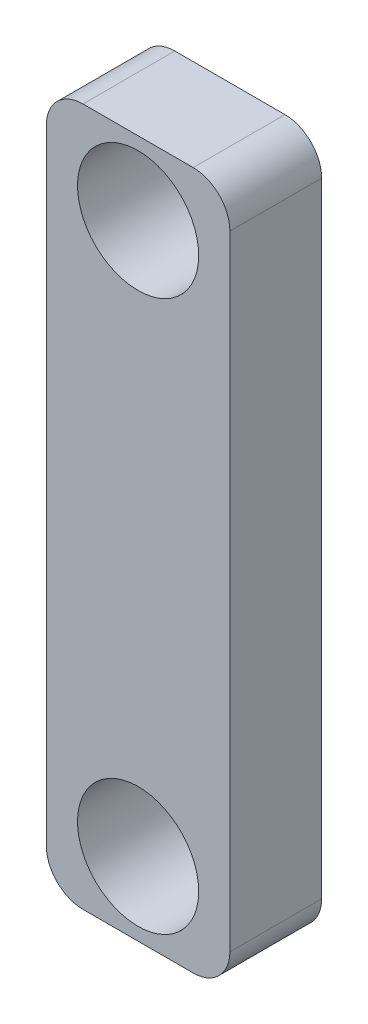
SolidWorks part; units mm, degrees
ref_plane "前视基准面" through (0, 0, 0) normal (0, 0, 1) x (1, 0, 0)
ref_plane "上视基准面" through (0, 0, 0) normal (0, 1, 0) x (1, 0, 0)
ref_plane "右视基准面" through (0, 0, 0) normal (1, 0, 0) x (0, 0, -1)
sketch "草图1" plane through (0, 0, 0) normal (0, 0, 1) x (1, 0, 0)
  line L1 (0, 0) -> (50, 0)
  line L2 (0, 0) -> (0, 190)
  line L3 (0, 190) -> (50, 190)
  line L4 (50, 0) -> (50, 190)
  circle A0 centre (25, 170) radius 16.5
  circle A1 centre (25, 20) radius 16.5
  dimension "D5" = 33
  dimension "D6" = 33
  dimension "D1" = 190
  dimension "D2" = 50
  dimension "D3" = 20
  dimension "D4" = 20
  dimension "D7" = 25
  dimension "D8" = 25
extrude "凸台-拉伸1" add sketch "草图1" along normal blind 25
fillet "圆角1" radius 10 4 edges at (50, 190, 12.5) (0, 190, 12.5) (0, 0, 12.5) (50, 0, 12.5)
